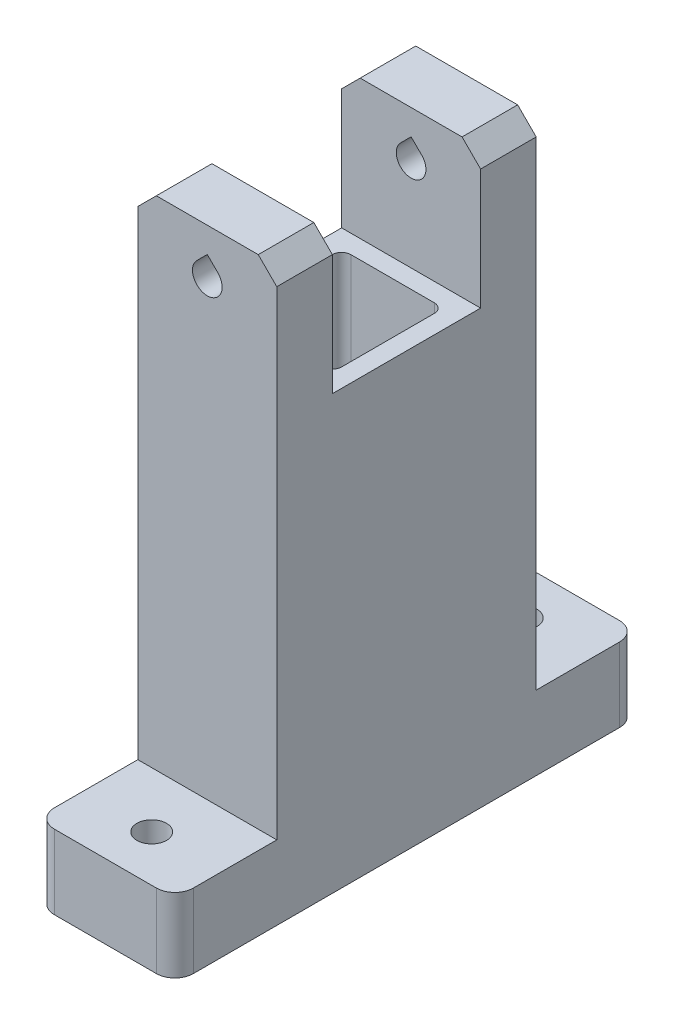
SolidWorks part; units mm, degrees
ref_plane "前视基准面" through (0, 0, 0) normal (0, 0, 1) x (1, 0, 0)
ref_plane "上视基准面" through (0, 0, 0) normal (0, 1, 0) x (1, 0, 0)
ref_plane "右视基准面" through (0, 0, 0) normal (1, 0, 0) x (0, 0, -1)
sketch "草图1" plane through (0, 0, 0) normal (0, 0, 1) x (1, 0, 0)
  line L0 (0, 508.744) -> (0, -508.744) construction
  line L1 (-508.744, 0) -> (508.744, 0) construction
  line L2 (7.5, 0) -> (-7.5, 0)
  line L3 (-7.5, 0) -> (-7.5, 61.71)
  line L4 (-7.5, 61.71) -> (7.5, 61.71)
  line L5 (0, 56.71) -> (-72.8886, 56.71) construction
  line L6 (0, 58.9727) -> (-1.1314, 57.8414)
  line L7 (0, 58.9727) -> (1.1314, 57.8414)
  line L8 (7.5, 0) -> (7.5, 61.71)
  arc A0 (-1.1314, 57.8414) -> (1.1314, 57.8414) centre (0, 56.71) ccw
  point P16 (0, 61.71)
  point P17 (0, 0)
  dimension "D2" = 3.2
  dimension "D1" = 56.71
  dimension "D3" = 45
  dimension "D4" = 5
  dimension "D5" = 15
extrude "凸台-拉伸1" add sketch "草图1" along normal mid plane 28
sketch "草图2" plane through (-7.5, 0, 0) normal (-1, 0, 0) x (0, 0, 1)
  line L0 (0, 0) -> (0, 84.6525) construction
  line L1 (-8, 61.71) -> (-8, 46.71)
  line L2 (14, 61.71) -> (-14, 61.71) construction
  line L3 (-8, 46.71) -> (8, 46.71)
  line L4 (-8, 61.71) -> (8, 61.71)
  line L5 (-14, 61.71) -> (-14, 0) construction
  line L6 (8, 61.71) -> (8, 46.71)
  point P12 (0, 61.71)
  point P13 (0, 46.71)
  dimension "D1" = 6
  dimension "D2" = 15
extrude "切除-拉伸1" cut sketch "草图2" against normal blind 28
sketch "草图3" plane through (0, 0, 0) normal (0, -1, 0) x (1, 0, 0)
  line L0 (0, 500) -> (0, -500) construction
  line L1 (-500, 0) -> (500, 0) construction
  line L2 (7.5, 14) -> (-7.5, 14)
  line L3 (-7.5, 14) -> (-7.5, 25)
  line L4 (-7.5, 25) -> (7.5, 25)
  line L5 (7.5, 14) -> (7.5, 25)
  line L6 (7.5, -14) -> (7.5, -25)
  line L7 (-7.5, -25) -> (7.5, -25)
  line L8 (-7.5, -14) -> (-7.5, -25)
  line L9 (7.5, -14) -> (-7.5, -14)
  circle A0 centre (0, 20) radius 1.6
  circle A1 centre (0, -20) radius 1.6
  point P12 (0, 25)
  point P20 (0, -25)
  dimension "D1" = 3.2
  dimension "D2" = 6
  dimension "D3" = 5
extrude "凸台-拉伸2" add sketch "草图3" against normal blind 8
sketch "草图4" plane through (0, 46.71, 0) normal (0, 1, 0) x (1, 0, 0)
  line L0 (7.5, 8) -> (7.5, -8) construction
  line L1 (4.5, -6) -> (-4.5, -6)
  line L2 (5.5, -5) -> (5.5, 5)
  line L3 (4.5, 6) -> (-4.5, 6)
  line L4 (-5.5, -5) -> (-5.5, 5)
  line L5 (5.5, -6) -> (-5.5, 6) construction
  line L6 (5.5, 6) -> (-5.5, -6) construction
  line L7 (-7.5, 8) -> (-7.5, -8) construction
  line L8 (7.5, 8) -> (-7.5, 8) construction
  arc A0 (-4.5, -6) -> (-5.5, -5) centre (-4.5, -5) cw
  arc A1 (5.5, 5) -> (4.5, 6) centre (4.5, 5) ccw
  arc A2 (4.5, -6) -> (5.5, -5) centre (4.5, -5) ccw
  arc A3 (-4.5, 6) -> (-5.5, 5) centre (-4.5, 5) ccw
  point P0 (0, 0)
  dimension "D4" = 1
  dimension "D1" = 2
  dimension "D2" = 2
  dimension "D3" = 2
extrude "切除-拉伸2" cut sketch "草图4" against normal blind 61
chamfer "倒角1" distance 2 angle 45 4 edges at (7.5, 61.71, -11) (-7.5, 61.71, -11) (7.5, 61.71, 11) (-7.5, 61.71, 11)
fillet "圆角1" radius 2 4 edges at (7.5, 4, 25) (-7.5, 4, 25) (7.5, 4, -25) (-7.5, 4, -25)
